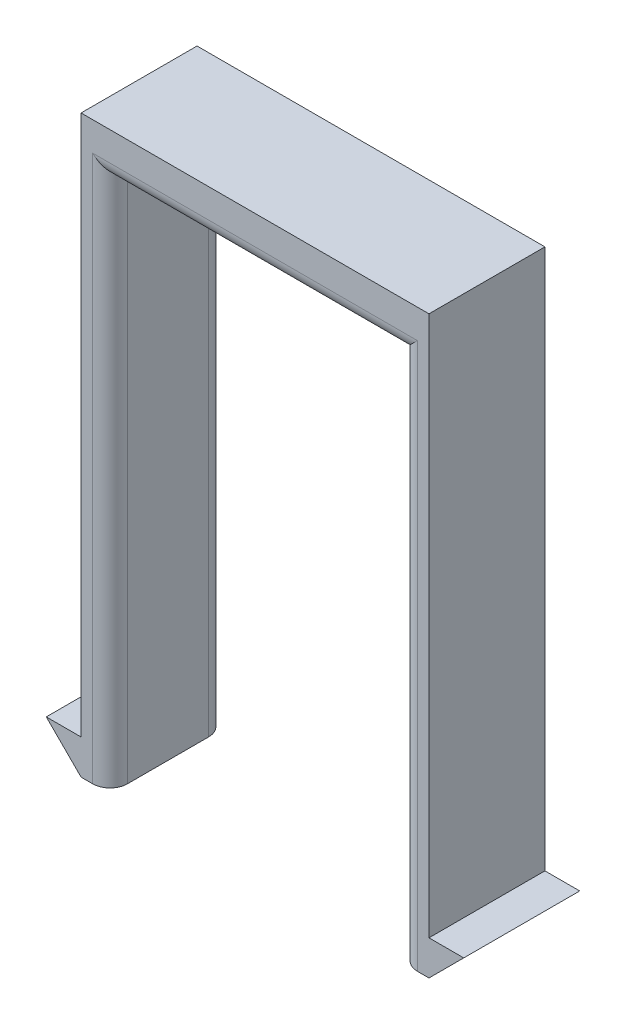
SolidWorks part; units mm, degrees
ref_plane "Front Plane" through (0, 0, 0) normal (0, 0, 1) x (1, 0, 0)
ref_plane "Top Plane" through (0, 0, 0) normal (0, 1, 0) x (1, 0, 0)
ref_plane "Right Plane" through (0, 0, 0) normal (1, 0, 0) x (0, 0, -1)
sketch "Sketch1" plane through (0, 0, 0) normal (0, 0, 1) x (1, 0, 0)
  line L1 (-12.5, -2) -> (12.5, -2)
  line L2 (-15, -2) -> (-15, 2)
  line L3 (-15, 2) -> (15, 2)
  line L4 (15, -2) -> (15, 2)
  line L5 (0, 0) -> (15, 2) construction
  line L6 (-15, 2) -> (0, 0) construction
  line L9 (-15, -47.6) -> (-12.5, -47.6)
  line L10 (-12.5, -2) -> (-12.5, -47.6)
  line L13 (15, -47.6) -> (12.5, -47.6)
  line L14 (12.5, -2) -> (12.5, -47.6)
  line L15 (-15, -2) -> (-15, -47.6)
  line L16 (15, -2) -> (15, -47.6)
  point P0 (0, 0)
  dimension "D1" = 30
  dimension "D2" = 4
  dimension "D3" = 45.6
  dimension "D4" = 2.5
  dimension "D5" = 45.6
  dimension "D6" = 2.5
extrude "Boss-Extrude1" add sketch "Sketch1" along normal blind 10
sketch "Sketch2" plane through (0, 0, 10) normal (0, 0, 1) x (1, 0, 0)
  line L0 (18, -44.6) -> (15, -47.6)
  line L2 (-15, -47.6) -> (-15, -44.6)
  line L3 (-15, -44.6) -> (-18, -44.6)
  line L6 (15, -47.6) -> (15, -44.6)
  line L7 (15, -44.6) -> (18, -44.6)
  line L9 (-18, -44.6) -> (-15, -47.6)
  dimension "D1" = 3
  dimension "D2" = 3
  dimension "D3" = 3
  dimension "D4" = 3
extrude "Boss-Extrude3" add sketch "Sketch2" against normal blind 10
fillet "Fillet3" radius 1.5 6 edges at (-12.5, -24.8, 0) (-12.5, -24.8, 10) (0, -2, 0) (0, -2, 10) (12.5, -24.8, 0) (12.5, -24.8, 10)
